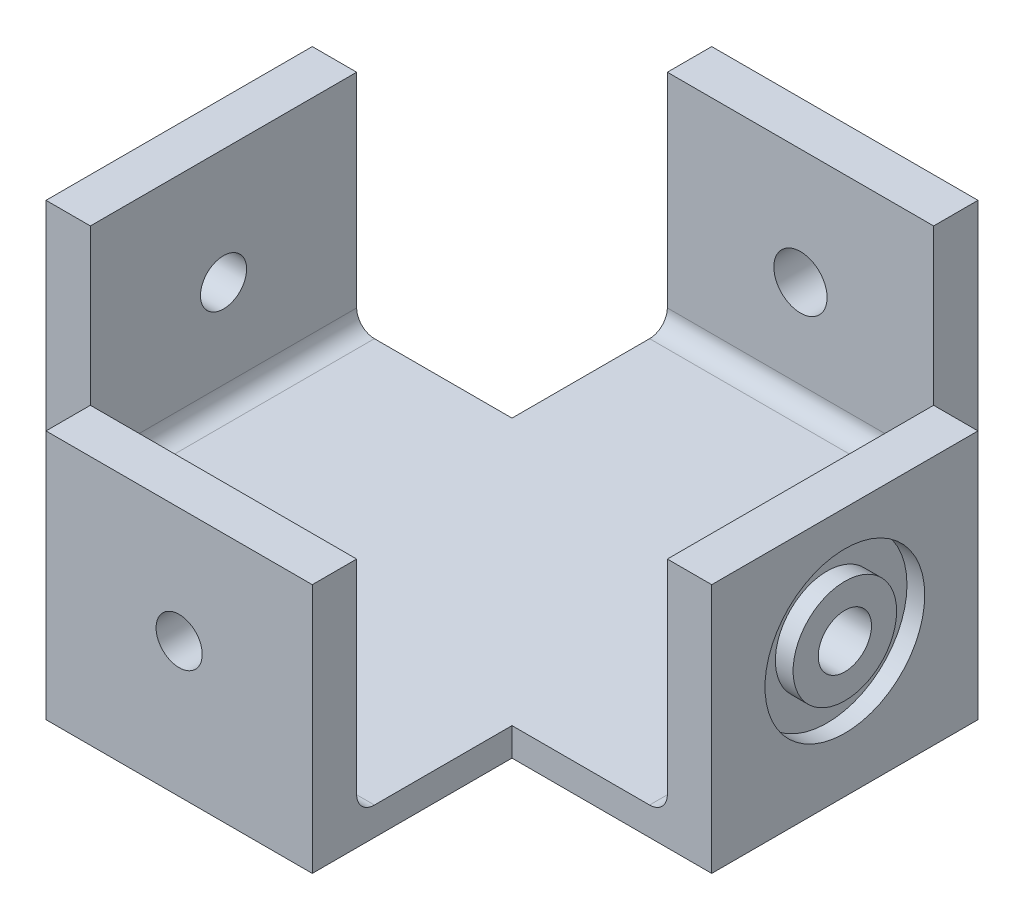
SolidWorks part; units mm, degrees
ref_plane "Front Plane" through (0, 0, 0) normal (0, 0, 1) x (1, 0, 0)
ref_plane "Top Plane" through (0, 0, 0) normal (0, 1, 0) x (1, 0, 0)
ref_plane "Right Plane" through (0, 0, 0) normal (1, 0, 0) x (0, 0, -1)
sketch "Sketch1" plane through (0, 0, 0) normal (0, 1, 0) x (1, 0, 0)
  line L0 (-15, 15) -> (-15, 37.5)
  line L1 (-37.5, -15) -> (-15, -15)
  line L2 (-37.5, -15) -> (-37.5, 15)
  line L3 (-37.5, 15) -> (-15, 15)
  line L4 (37.5, -15) -> (37.5, 15)
  line L5 (-37.5, -15) -> (37.5, 15) construction
  line L6 (-37.5, 15) -> (37.5, -15) construction
  line L7 (-15, -37.5) -> (15, -37.5)
  line L8 (-15, -37.5) -> (-15, -15)
  line L9 (-15, 37.5) -> (15, 37.5)
  line L10 (15, -37.5) -> (15, -15)
  line L11 (-15, -37.5) -> (15, 37.5) construction
  line L12 (-15, 37.5) -> (15, -37.5) construction
  line L13 (15, 15) -> (37.5, 15)
  line L14 (15, 15) -> (15, 37.5)
  line L15 (15, -15) -> (37.5, -15)
  point P0 (0, 0)
  point P6 (0, 0)
  dimension "D1" = 75
  dimension "D2" = 30
  dimension "D3" = 30
  dimension "D4" = 75
extrude "Boss-Extrude1" add sketch "Sketch1" along normal blind 3.175
sketch "Sketch4" plane through (0, 3.175, 0) normal (0, 1, 0) x (1, 0, 0)
  line L0 (37.5, 0) -> (-37.5, 0) construction
  line L1 (-37.5, -15) -> (-32.5, -15)
  line L2 (-37.5, -15) -> (-37.5, 15)
  line L3 (-37.5, 15) -> (-32.5, 15)
  line L4 (-32.5, -15) -> (-32.5, 15)
  line L5 (-37.5, -15) -> (-32.5, 15) construction
  line L6 (-37.5, 15) -> (-32.5, -15) construction
  line L7 (37.5, -15) -> (37.5, 15) construction
  line L8 (-37.5, 15) -> (-37.5, -15) construction
  line L9 (0, 37.5) -> (0, -37.5) construction
  line L10 (15, 37.5) -> (-15, 37.5) construction
  line L11 (-15, -37.5) -> (15, -37.5) construction
  line L12 (37.5, 15) -> (32.5, 15)
  line L13 (32.5, -15) -> (32.5, 15)
  line L14 (37.5, -15) -> (32.5, -15)
  line L15 (37.5, -15) -> (37.5, 15)
  point P0 (-35, 0)
  dimension "D1" = 5
  dimension "D2" = 30
  dimension "D3" = 37.5
extrude "Boss-Extrude3" add sketch "Sketch4" along normal blind 25
fillet "Fillet1" radius 2 2 edges at (32.5, 3.175, 0) (-32.5, 3.175, 0)
sketch "Sketch5" plane through (0, 3.175, 0) normal (0, 1, 0) x (1, 0, 0)
  line L0 (-15, -15) -> (-15, -37.5) construction
  line L1 (15, -37.5) -> (-15, -37.5)
  line L2 (15, -37.5) -> (15, -32.5)
  line L3 (15, -32.5) -> (-15, -32.5)
  line L4 (-15, -37.5) -> (-15, -32.5)
  line L5 (15, -37.5) -> (-15, -32.5) construction
  line L6 (15, -32.5) -> (-15, -37.5) construction
  line L7 (-30.5, 0) -> (30.5, 0) construction
  line L8 (-30.5, 15) -> (-30.5, -15) construction
  line L9 (30.5, -15) -> (30.5, 15) construction
  line L10 (15, 32.5) -> (-15, 32.5)
  line L11 (-15, 37.5) -> (-15, 32.5)
  line L12 (15, 37.5) -> (-15, 37.5)
  line L13 (15, 37.5) -> (15, 32.5)
  point P0 (0, -35)
  dimension "D1" = 37.5
  dimension "D2" = 5
  dimension "D3" = 30
extrude "Boss-Extrude4" add sketch "Sketch5" along normal blind 25
fillet "Fillet2" radius 2 2 edges at (0, 3.175, 32.5) (0, 3.175, -32.5)
sketch "Sketch6" plane through (-37.5, 0, 0) normal (-1, 0, 0) x (0, 0, 1)
  line L0 (0, 0) -> (0, 28.175) construction
  line L1 (-15, 0) -> (15, 0) construction
  line L2 (-15, 28.175) -> (15, 28.175) construction
  circle A0 centre (0, 15.175) radius 2.6
  dimension "D1" = 5.2
  dimension "D2" = 13
extrude "Cut-Extrude1" cut sketch "Sketch6" against normal blind 10
pattern_circular "CirPattern1" count 2 every 90 about axis through (0, 3.175, 0) along (0, 1, 0) of "Cut-Extrude1"
sketch "Sketch7" plane through (37.5, 0, 0) normal (1, 0, 0) x (0, 0, -1)
  line L0 (0, 0) -> (0, 27.3189) construction
  line L1 (-15, 0) -> (15, 0) construction
  line L2 (-15, 28.175) -> (15, 28.175) construction
  circle A0 centre (0, 15.175) radius 3
  dimension "D1" = 6
  dimension "D2" = 13
extrude "Cut-Extrude2" cut sketch "Sketch7" against normal blind 10
pattern_circular "CirPattern2" count 2 every 90 about axis through (0, 3.175, 0) along (0, 1, 0) of "Cut-Extrude2"
ref_plane "Plane1" through (0, 0, -35) normal (0, 0, -1) x (-1, 0, 0)
sketch "Sketch10" plane through (0, 0, -37.5) normal (0, 0, -1) x (-1, 0, 0)
  circle A0 centre (0, 15.175) radius 5.83
  circle A1 centre (0, 15.175) radius 9
  circle A2 centre (0, 15.175) radius 3 construction
  dimension "D1" = 3.17
  dimension "D2" = 18
extrude "Cut-Extrude9" cut sketch "Sketch10" against normal blind 2
pattern_circular "CirPattern4" count 2 every 270 about axis through (0, 3.175, 0) along (0, 1, 0) of "Cut-Extrude9"
